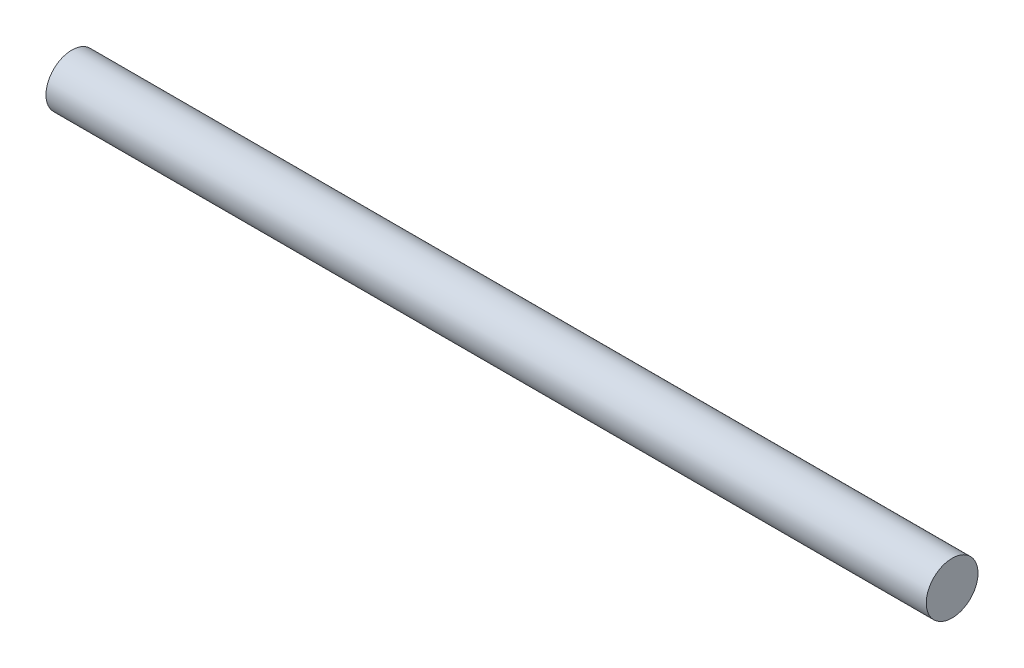
SolidWorks part; units mm, degrees
ref_plane "Front Plane" through (0, 0, 0) normal (0, 0, 1) x (1, 0, 0)
ref_plane "Top Plane" through (0, 0, 0) normal (0, 1, 0) x (1, 0, 0)
ref_plane "Right Plane" through (0, 0, 0) normal (1, 0, 0) x (0, 0, -1)
sketch "Sketch1" plane through (0, 0, 0) normal (1, 0, 0) x (0, 0, -1)
  circle A0 centre (0, 0) radius 2.54
  dimension "D1" = 5.08
extrude "Boss-Extrude1" add sketch "Sketch1" along normal blind 86.36 contours A0
